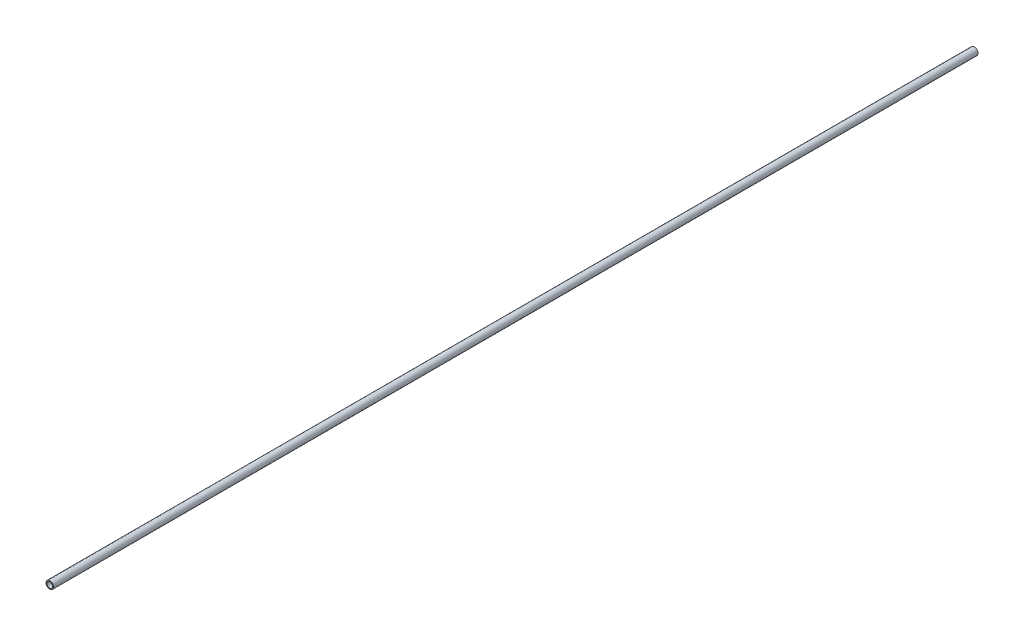
SolidWorks part; units mm, degrees
ref_plane "Front Plane" through (0, 0, 0) normal (0, 0, 1) x (1, 0, 0)
ref_plane "Top Plane" through (0, 0, 0) normal (0, 1, 0) x (1, 0, 0)
ref_plane "Right Plane" through (0, 0, 0) normal (1, 0, 0) x (0, 0, -1)
sketch "Sketch1" plane through (0, 0, 0) normal (0, 0, 1) x (1, 0, 0)
  circle A0 centre (0, 0) radius 4
  circle A1 centre (0, 0) radius 3
  dimension "D1" = 8
  dimension "D2" = 6
extrude "Boss-Extrude1" add sketch "Sketch1" along normal blind 990.6
